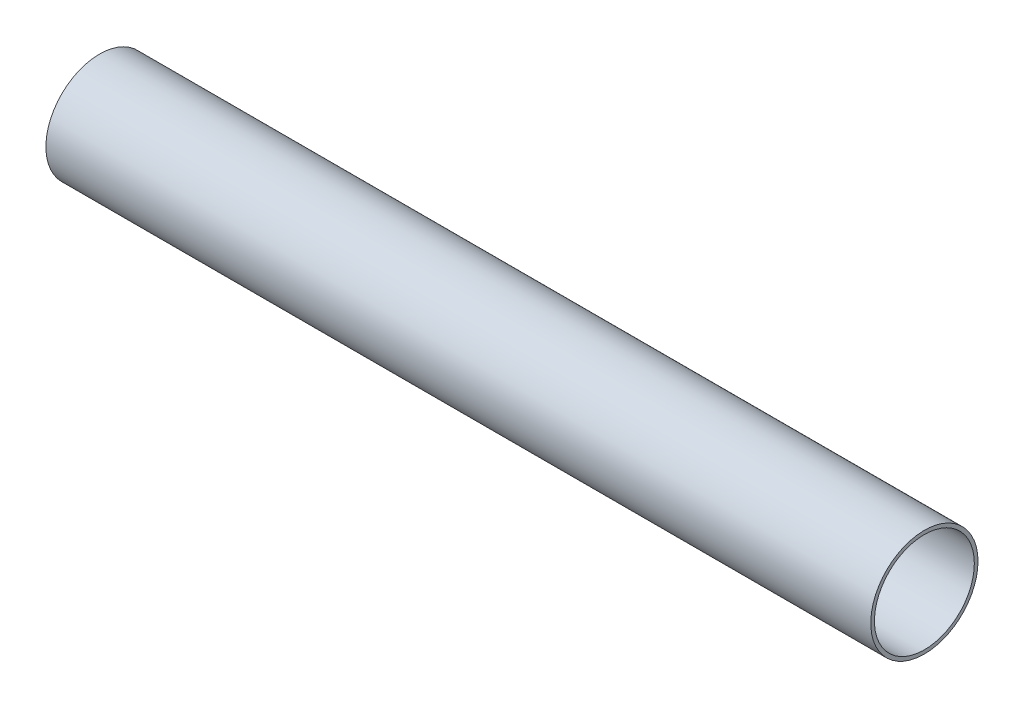
SolidWorks part; units mm, degrees
ref_plane "Front Plane" through (0, 0, 0) normal (0, 0, 1) x (1, 0, 0)
ref_plane "Top Plane" through (0, 0, 0) normal (0, 1, 0) x (1, 0, 0)
ref_plane "Right Plane" through (0, 0, 0) normal (1, 0, 0) x (0, 0, -1)
sketch "Sketch1" plane through (0, 0, 0) normal (1, 0, 0) x (0, 0, -1)
  circle A0 centre (-22.2709, -10.0874) radius 32.5
  circle A1 centre (-22.2709, -10.0874) radius 30.275
  dimension "D1" = 65
  dimension "D2" = 60.55
extrude "Boss-Extrude1" add sketch "Sketch1" along normal blind 500
equation "\"D1@Sketch1\"=69-4"
